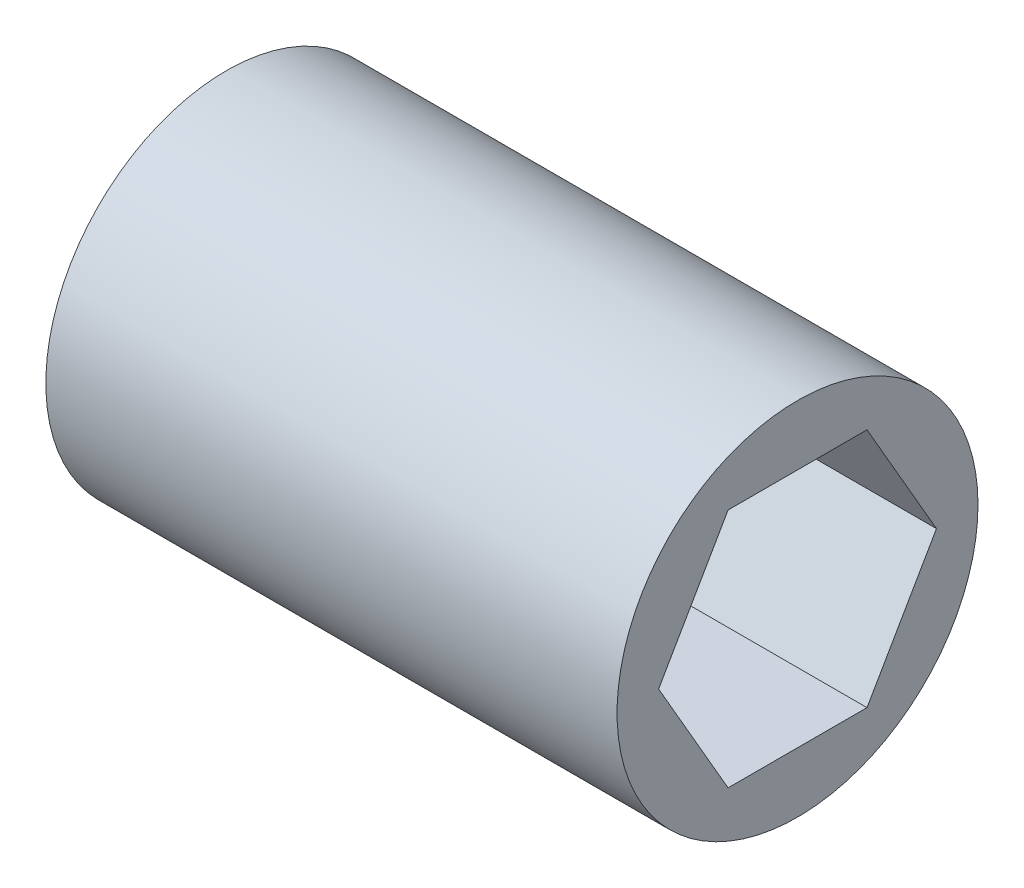
SolidWorks part; units mm, degrees
material "POM Acetal Copolymer"
ref_plane "Front Plane" through (0, 0, 0) normal (0, 0, 1) x (1, 0, 0)
ref_plane "Top Plane" through (0, 0, 0) normal (0, 1, 0) x (1, 0, 0)
ref_plane "Right Plane" through (0, 0, 0) normal (1, 0, 0) x (0, 0, -1)
sketch "Sketch1" plane through (0, 0, 0) normal (1, 0, 0) x (0, 0, -1)
  line L1 (7.3323, 0) -> (3.6662, 6.35)
  line L2 (3.6662, 6.35) -> (-3.6662, 6.35)
  line L3 (-3.6662, 6.35) -> (-7.3323, 0)
  line L4 (-7.3323, 0) -> (-3.6662, -6.35)
  line L5 (-3.6662, -6.35) -> (3.6662, -6.35)
  line L6 (3.6662, -6.35) -> (7.3323, 0)
  circle A0 centre (0, 0) radius 6.35 construction
  circle A1 centre (0, 0) radius 9.525
  dimension "D1" = 12.7
  dimension "D2" = 3.175
extrude "Boss-Extrude1" add sketch "Sketch1" along normal mid plane 30.15
